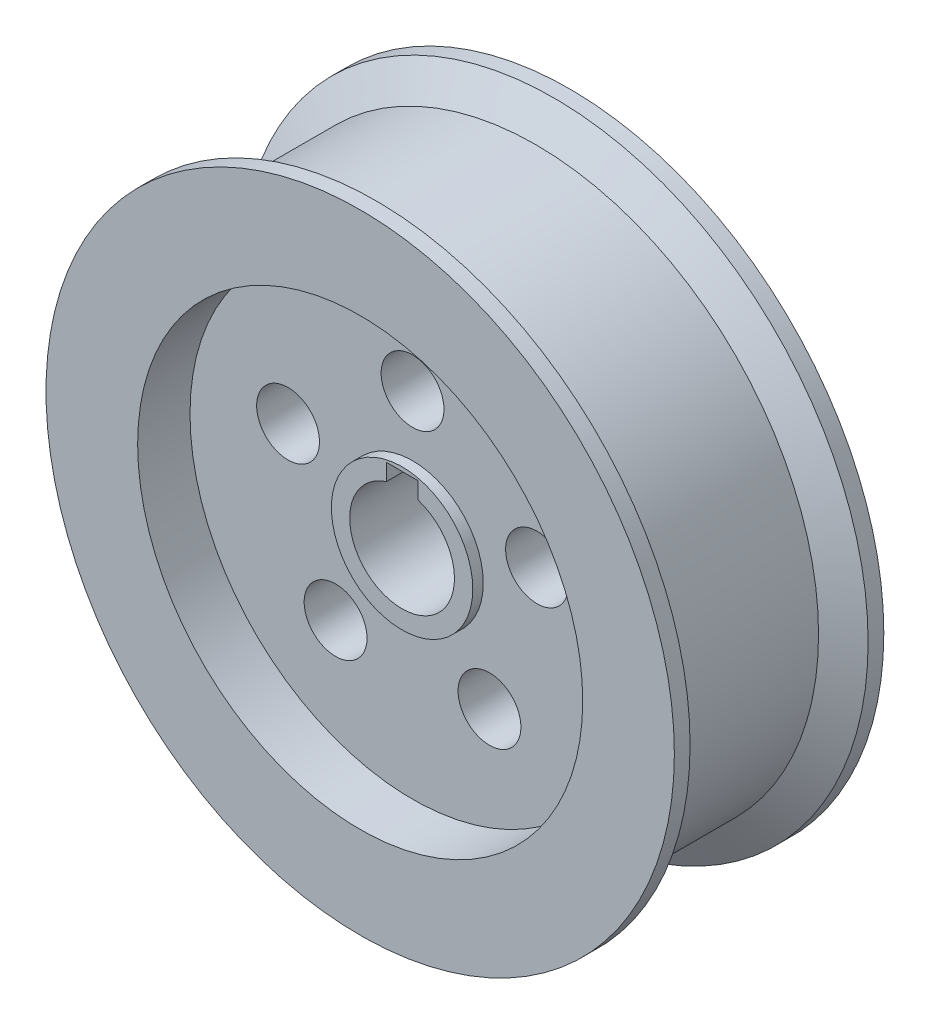
SolidWorks part; units mm, degrees
ref_plane "Front Plane" through (0, 0, 0) normal (0, 0, 1) x (1, 0, 0)
ref_plane "Top Plane" through (0, 0, 0) normal (0, 1, 0) x (1, 0, 0)
ref_plane "Right Plane" through (0, 0, 0) normal (1, 0, 0) x (0, 0, -1)
sketch "Sketch2" plane through (0, 0, 0) normal (0, 0, 1) x (1, 0, 0)
  circle A0 centre (0, 0) radius 60
  circle A1 centre (0, 0) radius 10
  dimension "D1" = 120
  dimension "D2" = 20
extrude "Boss-Extrude1" add sketch "Sketch2" along normal mid plane 40
sketch "Sketch3" plane through (0, 0, 20) normal (0, 0, 1) x (1, 0, 0)
  circle A0 centre (0, 0) radius 42.5
  dimension "D1" = 85
extrude "Cut-Extrude1" cut sketch "Sketch3" against normal blind 10
mirror "Mirror2" about plane through (0, 0, 0) normal (0, 0, 1) of "Cut-Extrude1"
sketch "Sketch4" plane through (0, 0, 10) normal (0, 0, 1) x (1, 0, 0)
  circle A0 centre (0, 25) radius 6
  dimension "D1" = 12
  dimension "D2" = 25
extrude "Cut-Extrude2" cut sketch "Sketch4" against normal through all both and the other way through all
pattern_circular "CirPattern2" count 5 over 360 about axis through (0, 0, 0) along (0, 0, 1) of "Cut-Extrude2"
sketch "Sketch5" plane through (0, 0, 0) normal (0, 1, 0) x (1, 0, 0)
  line L0 (0, 0) -> (0, 28.6742) construction
  line L1 (54, 13.5359) -> (60, 17)
  line L2 (60, -20) -> (60, 20) construction
  line L3 (60, 17) -> (60, -17)
  line L4 (60, -17) -> (54, -13.5359)
  line L5 (54, -13.5359) -> (54, 13.5359)
  line L6 (60, 20) -> (-60, 20) construction
  line L7 (-60, -20) -> (60, -20) construction
  dimension "D1" = 6
  dimension "D2" = 3
  dimension "D3" = 3
  dimension "D4" = 60
  dimension "D5" = 60
revolve "Cut-Revolve1" cut sketch "Sketch5" angle 360 about L0
sketch "Sketch6" plane through (0, 0, 10) normal (0, 0, 1) x (1, 0, 0)
  circle A0 centre (0, 0) radius 13.5
  circle A1 centre (0, 0) radius 10 construction
  circle A2 centre (0, 0) radius 10
  dimension "D1" = 27
extrude "Boss-Extrude3" add sketch "Sketch6" along normal blind 2 and the other way blind 7
sketch "Sketch8" plane through (0, 0, -10) normal (0, 0, -1) x (-1, 0, 0)
  line L1 (-3, 9.5169) -> (3, 9.5169)
  line L2 (-3, 9.5169) -> (-3, 12.7269)
  line L3 (-3, 12.7269) -> (3, 12.7269)
  line L4 (3, 9.5169) -> (3, 12.7269)
  line L5 (-3, 9.5169) -> (3, 12.7269) construction
  line L6 (-3, 12.7269) -> (3, 9.5169) construction
  point P0 (0, 11.1219)
  dimension "D1" = 3.21
  dimension "D2" = 6
extrude "Cut-Extrude3" cut sketch "Sketch8" against normal through all both and the other way through all
